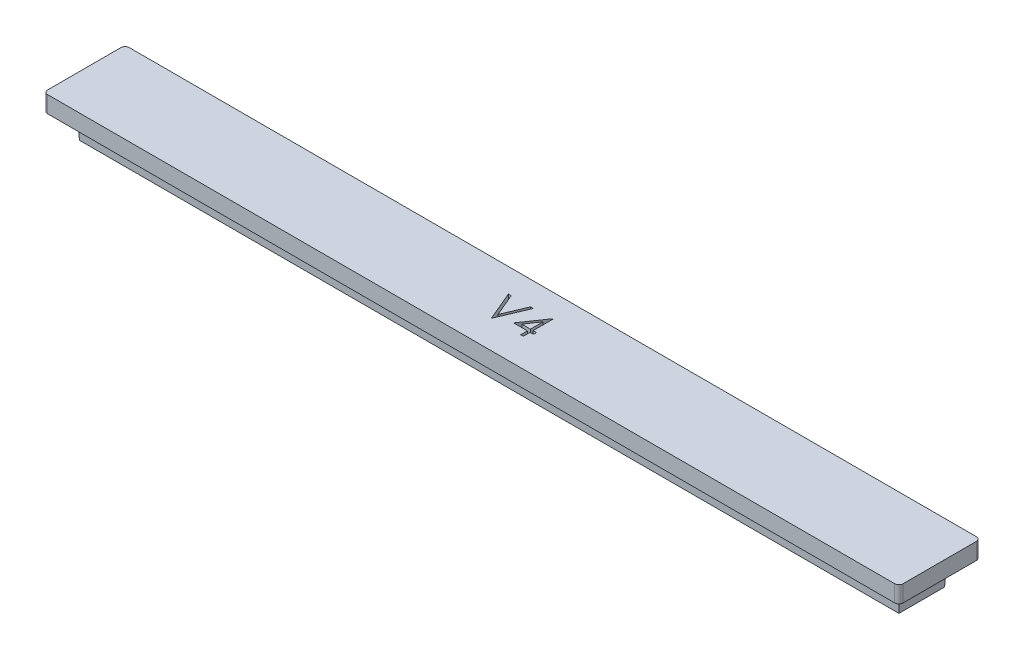
SolidWorks part; units mm, degrees
ref_plane "Front Plane" through (0, 0, 0) normal (0, 0, 1) x (1, 0, 0)
ref_plane "Top Plane" through (0, 0, 0) normal (0, 1, 0) x (1, 0, 0)
ref_plane "Right Plane" through (0, 0, 0) normal (1, 0, 0) x (0, 0, -1)
sketch "Sketch1" plane through (0, 0, 0) normal (0, 1, 0) x (1, 0, 0)
  line L1 (-49.4, 2.9) -> (49.4, 2.9)
  line L2 (-49.4, 2.9) -> (-49.4, -2.9)
  line L3 (-49.4, -2.9) -> (49.4, -2.9)
  line L4 (49.4, 2.9) -> (49.4, -2.9)
  line L5 (-49.4, 2.9) -> (49.4, -2.9) construction
  line L6 (-49.4, -2.9) -> (49.4, 2.9) construction
  point P0 (0, 0)
  dimension "D1" = 98.8
  dimension "D2" = 5.8
extrude "Boss-Extrude1" add sketch "Sketch1" along normal blind 3
sketch "Sketch2" plane through (0, 3, 0) normal (0, 1, 0) x (1, 0, 0)
  line L0 (50.4, -3.9) -> (50.4, 3.9)
  line L1 (50.4, 3.9) -> (-50.4, 3.9)
  line L2 (-50.4, 3.9) -> (-50.4, -3.9)
  line L3 (-50.4, -3.9) -> (50.4, -3.9)
  line L4 (49.4, -2.9) -> (49.4, 2.9)
  line L5 (49.4, 2.9) -> (-49.4, 2.9)
  line L6 (-49.4, 2.9) -> (-49.4, -2.9)
  line L7 (-49.4, -2.9) -> (49.4, -2.9)
  line L8 (49.4, -2.9) -> (49.4, 2.9) construction
  line L9 (49.4, 2.9) -> (-49.4, 2.9) construction
  line L10 (-49.4, 2.9) -> (-49.4, -2.9) construction
  line L11 (-49.4, -2.9) -> (49.4, -2.9) construction
  dimension "D1" = 0
  dimension "D2" = 1
extrude "Boss-Extrude3" add sketch "Sketch2" along normal blind 2 separate body
draft "Draft1" type of draft neutral plane draft angle 3 faces to draft 4 face at (49.4, 1.5, 0) face at (0, 1.5, 2.9) face at (-49.4, 1.5, 0) face at (0, 1.5, -2.9) neutral plane through (0, 3, 0) neutral plane normal (0, -1, 0) parameters "D1"=3
sketch "Sketch3" plane through (0, 5, 0) normal (0, 1, 0) x (1, 0, 0)
  line L0 (-51.4, -4.9) -> (51.4, -4.9)
  line L1 (51.4, -4.9) -> (51.4, 4.9)
  line L2 (51.4, 4.9) -> (-51.4, 4.9)
  line L3 (-51.4, 4.9) -> (-51.4, -4.9)
  line L4 (-50.4, -3.9) -> (50.4, -3.9)
  line L5 (50.4, -3.9) -> (50.4, 3.9)
  line L6 (50.4, 3.9) -> (-50.4, 3.9)
  line L7 (-50.4, 3.9) -> (-50.4, -3.9)
  line L8 (-50.4, -3.9) -> (50.4, -3.9)
  line L9 (50.4, -3.9) -> (50.4, 3.9)
  line L10 (50.4, 3.9) -> (-50.4, 3.9)
  line L11 (-50.4, 3.9) -> (-50.4, -3.9)
  dimension "D1" = 0
  dimension "D2" = 1
extrude "Boss-Extrude4" add sketch "Sketch3" against normal blind 2
fillet "Fillet1" radius 0.5 4 edges at (-51.4, 4, -4.9) (51.4, 4, -4.9) (51.4, 4, 4.9) (-51.4, 4, 4.9)
sketch "Sketch4" plane through (0, 5, 0) normal (0, 1, 0) x (1, 0, 0)
  text T1 "V4\r\n\r\n"
extrude "Cut-Extrude1" cut sketch "Sketch4" against normal blind 1
sketch "Sketch5" plane through (0, 3, 0) normal (0, -1, 0) x (1, 0, 0)
  line L4 (-51.4, 4.4) -> (-51.4, -4.4)
  line L5 (-50.9, -4.9) -> (50.9, -4.9)
  line L6 (51.4, -4.4) -> (51.4, 4.4)
  line L7 (50.9, 4.9) -> (-50.9, 4.9)
  line L8 (-51.4, 4.4) -> (-51.4, -4.4)
  line L9 (-50.9, -4.9) -> (50.9, -4.9)
  line L10 (51.4, -4.4) -> (51.4, 4.4)
  line L11 (50.9, 4.9) -> (-50.9, 4.9)
  arc A4 (-51.4, -4.4) -> (-50.9, -4.9) centre (-50.9, -4.4) ccw
  arc A5 (50.9, -4.9) -> (51.4, -4.4) centre (50.9, -4.4) ccw
  arc A6 (51.4, 4.4) -> (50.9, 4.9) centre (50.9, 4.4) ccw
  arc A7 (-50.9, 4.9) -> (-51.4, 4.4) centre (-50.9, 4.4) ccw
  arc A8 (-51.4, -4.4) -> (-50.9, -4.9) centre (-50.9, -4.4) ccw
  arc A9 (50.9, -4.9) -> (51.4, -4.4) centre (50.9, -4.4) ccw
  arc A10 (51.4, 4.4) -> (50.9, 4.9) centre (50.9, 4.4) ccw
  arc A11 (-50.9, 4.9) -> (-51.4, 4.4) centre (-50.9, 4.4) ccw
  dimension "D1" = 0
extrude "Cut-Extrude2" [suppressed] cut sketch "Sketch5" along normal blind 10
sketch "Sketch6" plane through (0, 5, 0) normal (0, 1, 0) x (1, 0, 0)
  line L0 (50.9, 4.9) -> (-50.9, 4.9) construction
  line L1 (-48.4, 1.9) -> (48.4, 1.9)
  line L2 (-48.4, 1.9) -> (-48.4, -1.9)
  line L3 (-48.4, -1.9) -> (48.4, -1.9)
  line L4 (48.4, 1.9) -> (48.4, -1.9)
  line L5 (-48.4, 1.9) -> (48.4, -1.9) construction
  line L6 (-48.4, -1.9) -> (48.4, 1.9) construction
  line L8 (-51.4, 4.4) -> (-51.4, -4.4) construction
  point P0 (0, 0)
  dimension "D1" = 3
  dimension "D2" = 3
extrude "Cut-Extrude3" [suppressed] cut sketch "Sketch6" against normal blind 3
